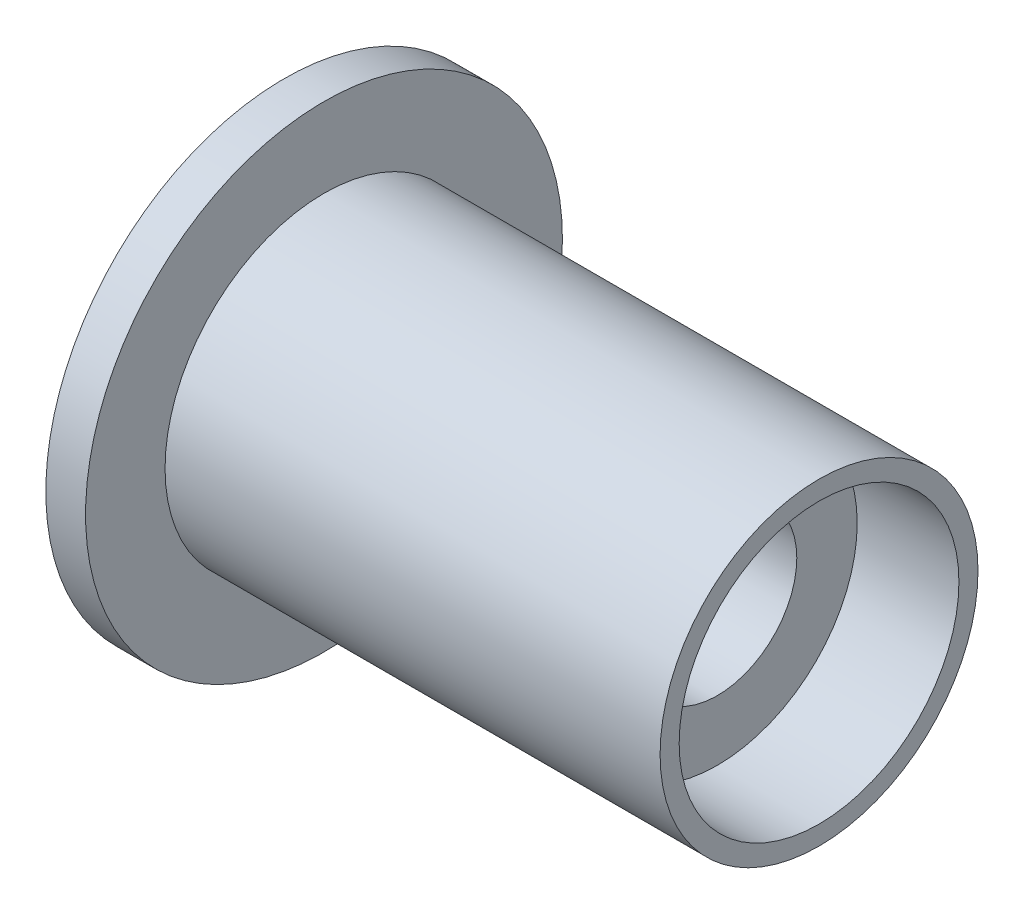
SolidWorks part; units mm, degrees
ref_plane "Front Plane" through (0, 0, 0) normal (0, 0, 1) x (1, 0, 0)
ref_plane "Top Plane" through (0, 0, 0) normal (0, 1, 0) x (1, 0, 0)
ref_plane "Right Plane" through (0, 0, 0) normal (1, 0, 0) x (0, 0, -1)
sketch "Sketch1" plane through (0, 0, 0) normal (0, 0, 1) x (1, 0, 0)
  line L0 (0, 0) -> (0, 9.525)
  line L1 (0, 9.525) -> (1.5875, 9.525)
  line L2 (1.5875, 9.525) -> (1.5875, 6.35)
  line L3 (1.5875, 6.35) -> (21.3639, 6.35)
  line L4 (21.3639, 6.35) -> (21.3639, 0)
  line L5 (21.3639, 0) -> (0, 0)
  line L6 (21.3639, 0) -> (21.3639, 5.588)
  line L7 (21.3639, 5.588) -> (17.2999, 5.588)
  line L8 (17.2999, 5.588) -> (17.2999, 3.175)
  line L9 (17.2999, 3.175) -> (0, 3.175)
  dimension "D1" = 9.525
  dimension "D2" = 6.35
  dimension "D3" = 4.064
  dimension "D4" = 19.7764
  dimension "D5" = 1.5875
  dimension "D6" = 3.175
revolve "Revolve1" add sketch "Sketch1" angle 360 about L5
